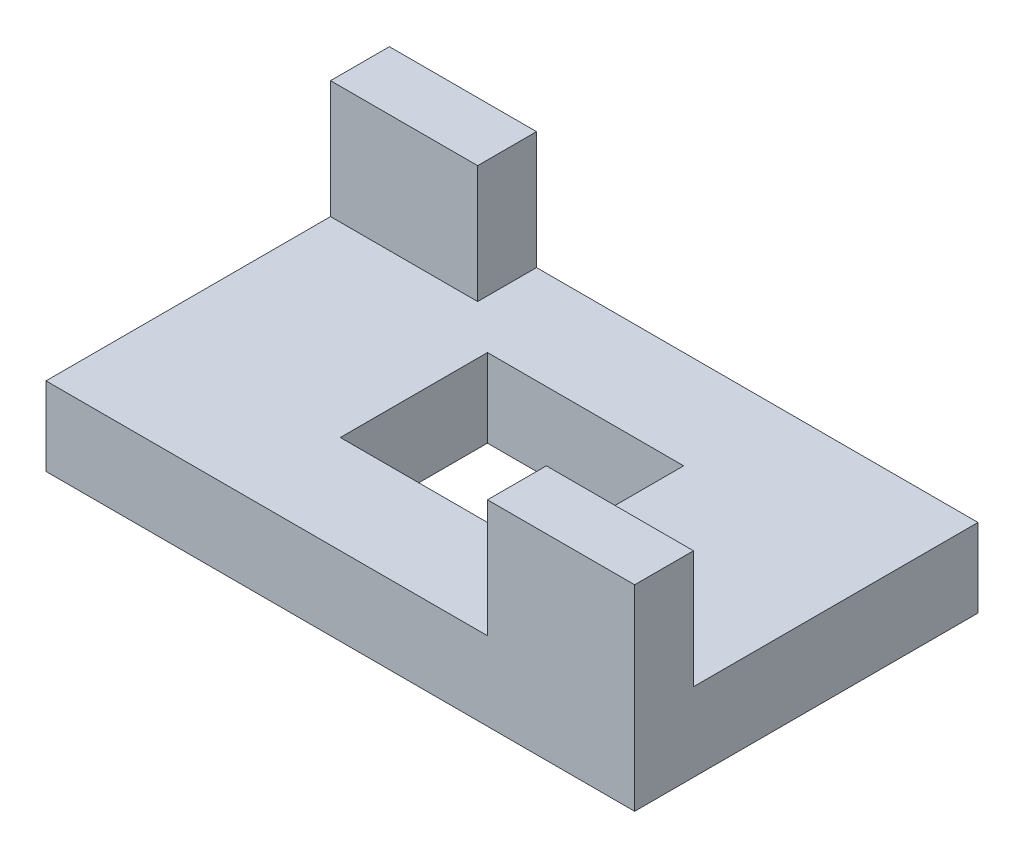
SolidWorks part; units mm, degrees
material "1060 Alloy"
ref_plane "Front Plane" through (0, 0, 0) normal (0, 0, 1) x (1, 0, 0)
ref_plane "Top Plane" through (0, 0, 0) normal (0, 1, 0) x (1, 0, 0)
ref_plane "Right Plane" through (0, 0, 0) normal (1, 0, 0) x (0, 0, -1)
sketch "Sketch1" plane through (0, 0, 0) normal (0, 1, 0) x (1, 0, 0)
  line L1 (-30, 17.5) -> (30, 17.5)
  line L2 (-30, 17.5) -> (-30, -17.5)
  line L3 (-30, -17.5) -> (30, -17.5)
  line L4 (30, 17.5) -> (30, -17.5)
  line L5 (-30, 17.5) -> (30, -17.5) construction
  line L6 (-30, -17.5) -> (30, 17.5) construction
  point P0 (0, 0)
  dimension "D1" = 60
  dimension "D2" = 35
  dimension "D3" = 30
  dimension "D4" = 17.5
extrude "Boss-Extrude1" add sketch "Sketch1" along normal blind 8
sketch "Sketch2" plane through (0, 0, 0) normal (0, 1, 0) x (1, 0, 0)
  line L0 (30, 17.5) -> (-30, 17.5) construction
  line L1 (-10, 7.5) -> (10, 7.5)
  line L2 (-10, 7.5) -> (-10, -7.5)
  line L3 (-10, -7.5) -> (10, -7.5)
  line L4 (10, 7.5) -> (10, -7.5)
  line L5 (-10, 7.5) -> (10, -7.5) construction
  line L6 (-10, -7.5) -> (10, 7.5) construction
  line L7 (30, -17.5) -> (30, 17.5) construction
  point P0 (0, 0)
  dimension "D1" = 10
  dimension "D2" = 20
extrude "Cut-Extrude1" cut sketch "Sketch2" along normal through all
sketch "Sketch3" plane through (0, 0, 0) normal (0, 1, 0) x (1, 0, 0)
  line L0 (30, -11.5) -> (15, -11.5)
  line L1 (-30, 17.5) -> (-15, 17.5)
  line L2 (-30, 17.5) -> (-30, 11.5)
  line L3 (-30, 11.5) -> (-15, 11.5)
  line L4 (-15, 17.5) -> (-15, 11.5)
  line L7 (30, -11.5) -> (30, -17.5)
  line L8 (30, -17.5) -> (15, -17.5)
  line L9 (15, -11.5) -> (15, -17.5)
  point P10 (30, -17.5)
  point P11 (15.5555, -12.9737)
  dimension "D1" = 15
  dimension "D2" = 6
  dimension "D3" = 15
  dimension "D4" = 6
extrude "Boss-Extrude2" add sketch "Sketch3" along normal blind 20
